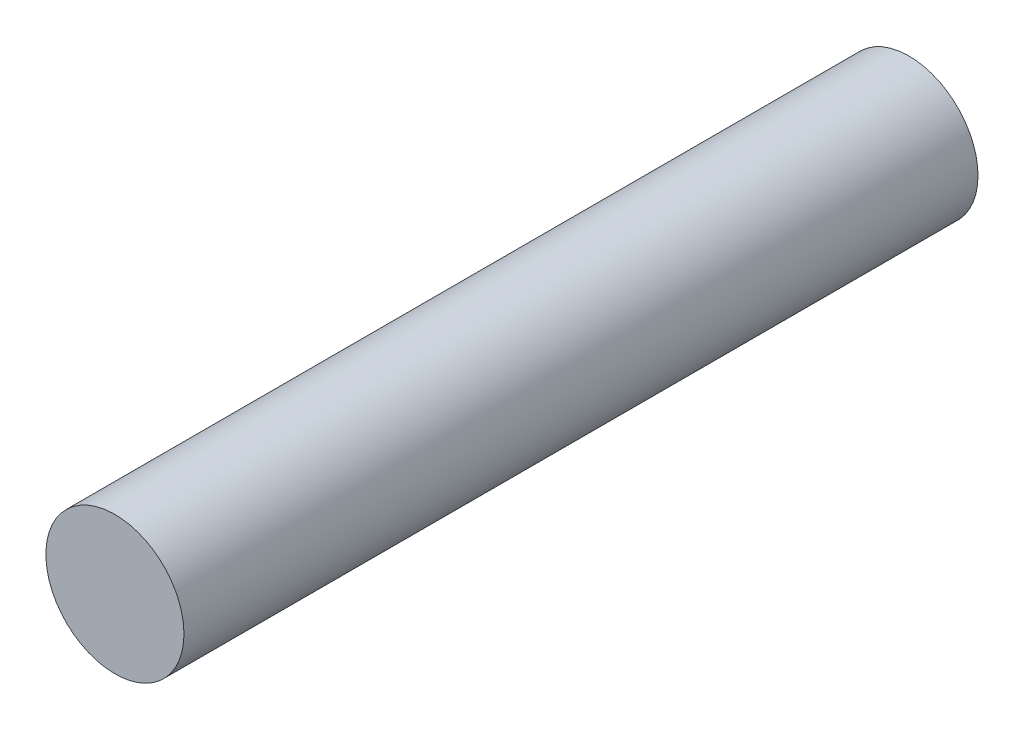
SolidWorks part; units mm, degrees
ref_plane "前视基准面" through (0, 0, 0) normal (0, 0, 1) x (1, 0, 0)
ref_plane "上视基准面" through (0, 0, 0) normal (0, 1, 0) x (1, 0, 0)
ref_plane "右视基准面" through (0, 0, 0) normal (1, 0, 0) x (0, 0, -1)
sketch "草图1" plane through (0, 0, 0) normal (0, 0, 1) x (1, 0, 0)
  circle A0 centre (0, 0) radius 2
  dimension "D1" = 4
extrude "凸台-拉伸1" add sketch "草图1" along normal blind 10
sketch "草图2" plane through (0, 0, 10) normal (0, 0, 1) x (1, 0, 0)
  circle A0 centre (0, 0) radius 2
  dimension "D1" = 4
extrude "凸台-拉伸2" add sketch "草图2" along normal blind 13
